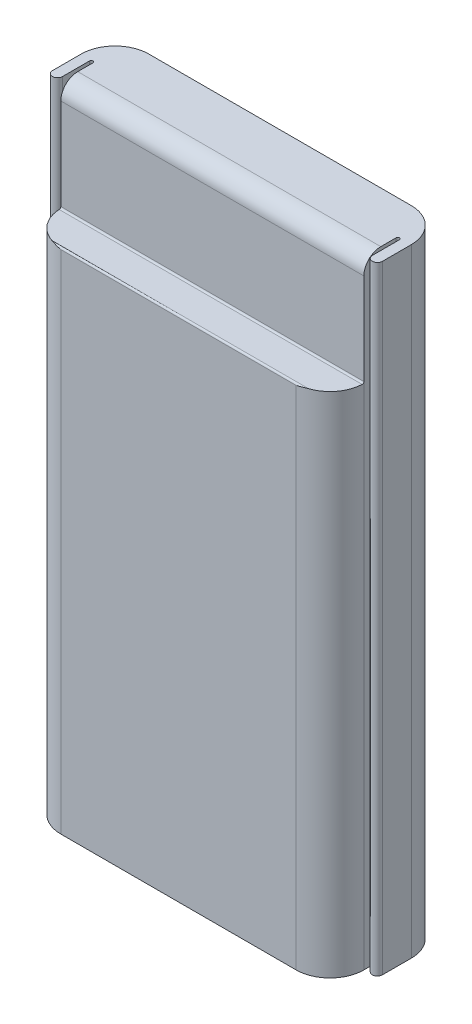
SolidWorks part; units mm, degrees
ref_plane "Front" through (0, 0, 0) normal (0, 0, 1) x (1, 0, 0)
ref_plane "Top" through (0, 0, 0) normal (0, 1, 0) x (1, 0, 0)
ref_plane "Right" through (0, 0, 0) normal (1, 0, 0) x (0, 0, -1)
sketch "Эскиз1" plane through (0, 0, 0) normal (0, 1, 0) x (1, 0, 0)
  line L0 (-7.75, 0) -> (7.75, 0)
  line L1 (-6.95, -6) -> (6.95, -6)
  line L2 (-9.75, -2) -> (-9.75, -3.7)
  line L3 (9.75, -2) -> (9.75, -3.7)
  line L4 (-8.95, -4) -> (-8.95, -2.1)
  line L5 (8.95, -2.1) -> (8.95, -4)
  line L6 (9.15, -3.7) -> (9.15, -2.1)
  line L7 (-9.15, -3.7) -> (-9.15, -2.1)
  arc A0 (-7.75, 0) -> (-9.75, -2) centre (-7.75, -2) ccw
  arc A1 (7.75, 0) -> (9.75, -2) centre (7.75, -2) cw
  arc A2 (-8.95, -4) -> (-6.95, -6) centre (-6.95, -4) ccw
  arc A3 (8.95, -4) -> (6.95, -6) centre (6.95, -4) cw
  arc A4 (9.75, -3.7) -> (9.15, -3.7) centre (9.45, -3.7) cw
  arc A5 (8.95, -2.1) -> (9.15, -2.1) centre (9.05, -2.1) cw
  arc A6 (-9.75, -3.7) -> (-9.15, -3.7) centre (-9.45, -3.7) ccw
  arc A7 (-8.95, -2.1) -> (-9.15, -2.1) centre (-9.05, -2.1) ccw
  point P20 (9.05, -2)
  point P21 (9.45, -4)
  point P27 (-9.05, -2)
  point P28 (-9.45, -4)
  dimension "D1" = 19.5
  dimension "D3" = 2
  dimension "D4" = 2
  dimension "D5" = 0.3
  dimension "D6" = 0.1
  dimension "D2" = 6
extrude "Бобышка-Вытянуть1" add sketch "Эскиз1" along normal mid plane 36.5
sketch "Эскиз2" plane through (0, 0, 0) normal (1, 0, 0) x (0, 0, -1)
  line L0 (-4, 17.25) -> (-4, 11.85)
  line L1 (-4.1, 11.75) -> (-5.9, 11.75)
  line L2 (-6, 18.25) -> (-6, 11.65)
  line L3 (-6, 18.25) -> (-6, -18.25) construction
  line L6 (-6, 18.25) -> (-3, 18.25)
  line L7 (0, 18.25) -> (-2, 18.25) construction
  arc A0 (-4, 11.85) -> (-4.1, 11.75) centre (-4.1, 11.85) cw
  arc A1 (-5.9, 11.75) -> (-6, 11.65) centre (-5.9, 11.65) ccw
  arc A2 (-3, 18.25) -> (-4, 17.25) centre (-3, 17.25) ccw
  dimension "D1" = 0.1
  dimension "D4" = 1
  dimension "D2" = 4
  dimension "D3" = 6.5
extrude "Вырез-Вытянуть1" cut sketch "Эскиз2" against normal up to next and the other way up to next
